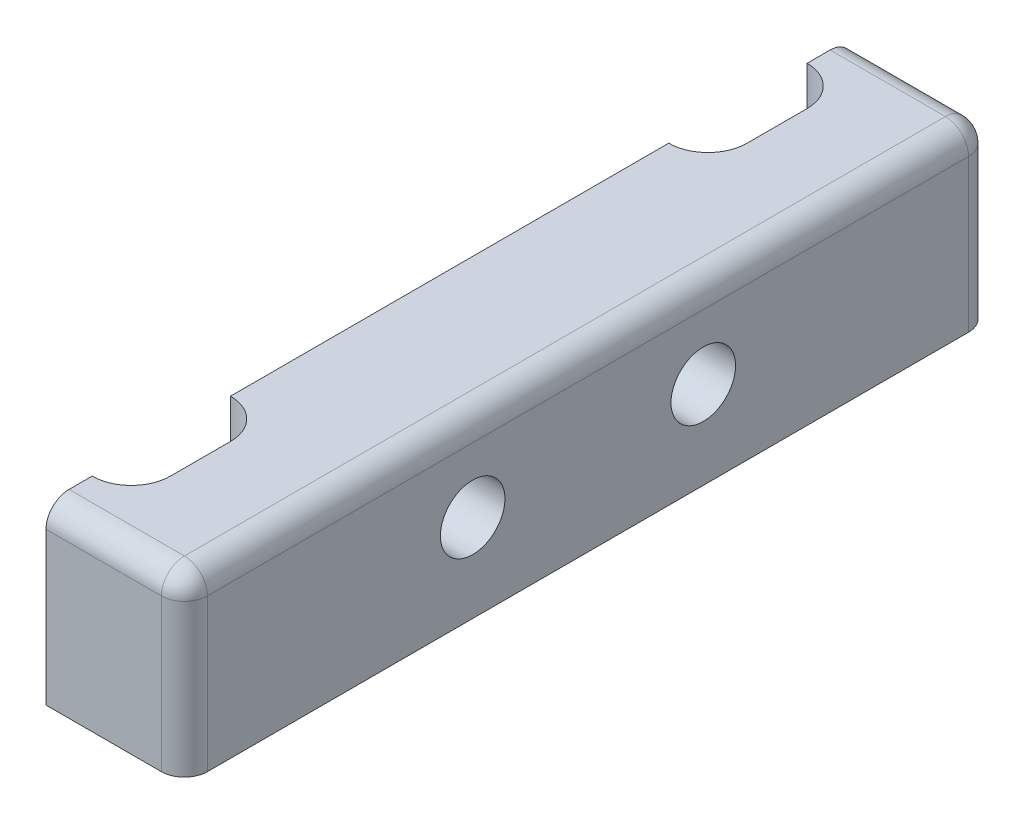
SolidWorks part; units mm, degrees
ref_plane "Front Plane" through (0, 0, 0) normal (0, 0, 1) x (1, 0, 0)
ref_plane "Top Plane" through (0, 0, 0) normal (0, 1, 0) x (1, 0, 0)
ref_plane "Right Plane" through (0, 0, 0) normal (1, 0, 0) x (0, 0, -1)
sketch "Sketch1" plane through (0, 0, 0) normal (0, 1, 0) x (1, 0, 0)
  line L0 (-6, 17.5) -> (-6, 15.5)
  line L1 (-6, 17.5) -> (0, 17.5)
  line L3 (-6, -17.5) -> (0, -17.5)
  line L4 (0, 17.5) -> (0, -17.5)
  line L5 (-6, 9.5) -> (-6, -9.5)
  line L6 (-6, -17.5) -> (-6, -15.5)
  line L7 (-4.3, -13.8) -> (-4.3, -11.2)
  line L8 (-4.3, 11.2) -> (-4.3, 13.8)
  arc A0 (-4.3, 13.8) -> (-6, 15.5) centre (-6, 13.8) ccw
  arc A1 (-4.3, 11.2) -> (-6, 9.5) centre (-6, 11.2) cw
  arc A2 (-4.3, -11.2) -> (-6, -9.5) centre (-6, -11.2) ccw
  arc A3 (-4.3, -13.8) -> (-6, -15.5) centre (-6, -13.8) cw
  point P4 (0, 0)
  point P18 (0, 0)
  point P19 (-6.6863, 15.5307)
  point P20 (-4.3, 12.5)
  point P21 (-4.3, -12.5)
  point P22 (-5.3, 6.5882)
  point P23 (-7, 15.0991)
  dimension "D4" = 1.7
  dimension "D1" = 35
  dimension "D2" = 6
  dimension "D3" = 2
  dimension "D5" = 6
  dimension "D6" = 2.6
  dimension "D7" = 25
  dimension "D8" = 6
extrude "Base" add sketch "Sketch1" along normal blind 7.6
sketch "Sketch2" plane through (-6, 0, 0) normal (-1, 0, 0) x (0, 0, 1)
  line L0 (-9.5, 3.8) -> (9.5, 3.8) construction
  line L1 (-9.5, 7.6) -> (-9.5, 0) construction
  line L2 (9.5, 7.6) -> (9.5, 0) construction
  line L3 (0, 7.6) -> (0, 0) construction
  line L4 (-9.5, 7.6) -> (9.5, 7.6) construction
  circle A0 centre (-5, 3.8) radius 1.4
  circle A1 centre (5, 3.8) radius 1.4
  dimension "D1" = 4.5
  dimension "D2" = 2.8
extrude "Screw Holes" cut sketch "Sketch2" against normal through all
fillet "1mm Edge Fillets" radius 1 5 edges at (0, 3.8, -17.5) (-3, 7.6, -17.5) (0, 7.6, 0) (0, 3.8, 17.5) (-3, 7.6, 17.5)
